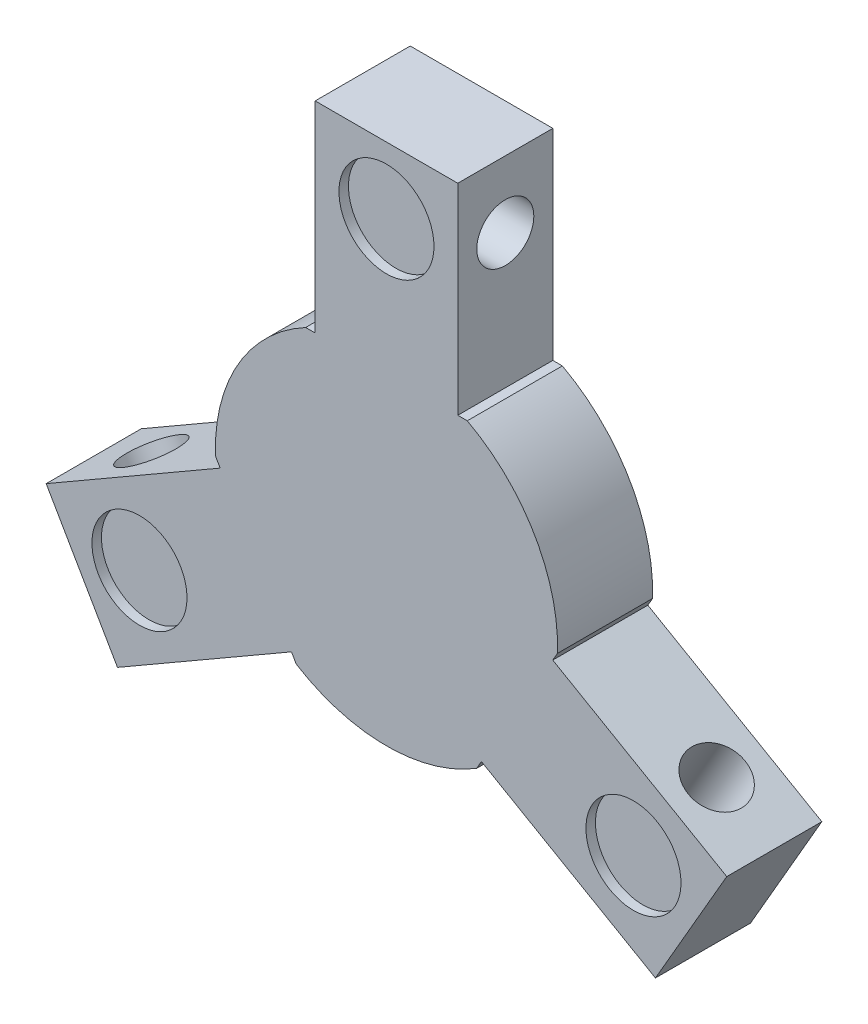
SolidWorks part; units mm, degrees
ref_plane "前视基准面" through (0, 0, 0) normal (0, 0, 1) x (1, 0, 0)
ref_plane "上视基准面" through (0, 0, 0) normal (0, 1, 0) x (1, 0, 0)
ref_plane "右视基准面" through (0, 0, 0) normal (1, 0, 0) x (0, 0, -1)
sketch "草图1" plane through (0, 0, 0) normal (0, 0, 1) x (1, 0, 0)
  line L4 (5, 7.4833) -> (5, 18.0033)
  line L5 (-8.9807, 0.5885) -> (-18.0885, -4.6699)
  line L6 (-3.9807, -8.0718) -> (-13.0885, -13.3301)
  line L7 (3.9807, -8.0718) -> (13.0885, -13.3301)
  line L9 (-5, 18.0033) -> (5, 18.0033)
  line L10 (-18.0885, -4.6699) -> (-13.0885, -13.3301)
  line L11 (18.0885, -4.6699) -> (13.0885, -13.3301)
  line L18 (8.9807, 0.5885) -> (18.0885, -4.6699)
  line L21 (-5, 7.4833) -> (-5, 18.0033)
  arc A0 (-5, 7.4833) -> (-8.9807, 0.5885) centre (0, 0) ccw
  arc A1 (-3.9807, -8.0718) -> (3.9807, -8.0718) centre (0, 0) ccw
  arc A2 (8.9807, 0.5885) -> (5, 7.4833) centre (0, 0) ccw
  dimension "D1" = 18
  dimension "D2" = 10.52
extrude "凸台-拉伸1" add sketch "草图1" along normal blind 5 contours L18 A2 L4 L9 L21 A0 L5 L10 L6 A1 L7 L11
sketch "草图2" plane through (5, 0, 0) normal (1, 0, 0) x (0, 0, -1)
  circle A0 centre (-2.5, 15.0033) radius 1.5
  dimension "D1" = 3
  dimension "D2" = 2.5
  dimension "D3" = 3
extrude "切除-拉伸1" cut sketch "草图2" against normal blind 10
sketch "草图3" plane through (-2.5, -4.3301, 0) normal (-0.5, -0.866, 0) x (0.866, -0.5, 0)
  circle A0 centre (15, 2.5) radius 1.5
  dimension "D1" = 3
  dimension "D2" = 2.5
  dimension "D3" = 3
extrude "切除-拉伸2" cut sketch "草图3" against normal blind 10
sketch "草图4" plane through (2.5, -4.3301, 0) normal (0.5, -0.866, 0) x (0.866, 0.5, 0)
  line L0 (-18, 5) -> (-18, 0) construction
  circle A0 centre (-15, 2.5) radius 1.5
  dimension "D1" = 3
  dimension "D2" = 3
  dimension "D3" = 2.5
extrude "切除-拉伸3" cut sketch "草图4" against normal blind 10
sketch "草图5" plane through (0, 0, 5) normal (0, 0, 1) x (1, 0, 0)
  line L1 (-4, 0) -> (-2, -3.4641)
  line L2 (-2, -3.4641) -> (2, -3.4641)
  line L3 (2, -3.4641) -> (4, 0)
  line L4 (4, 0) -> (2, 3.4641)
  line L5 (2, 3.4641) -> (-2, 3.4641)
  line L6 (-2, 3.4641) -> (-4, 0)
  circle A1 centre (0, 0) radius 3.4641 construction
  dimension "D1" = 4
extrude "切除-拉伸4" cut sketch "草图5" against normal blind 3
sketch "草图6" plane through (0, 0, 5) normal (0, 0, 1) x (1, 0, 0)
  circle A0 centre (0, 0) radius 2.5
  dimension "D1" = 5
extrude "切除-拉伸5" cut sketch "草图6" against normal blind 5
sketch "草图8" plane through (0, 0, 5) normal (0, 0, 1) x (1, 0, 0)
  line L2 (-8.7057, 0.1122) -> (-17.8135, -5.1462)
  line L3 (-8.9998, -0.0576) -> (-17.8135, -5.1462)
  line L5 (-4.2557, -7.5955) -> (-13.3635, -12.8538)
  line L6 (-4.5498, -7.7653) -> (-13.3635, -12.8538)
  line L8 (-4.45, 7.4833) -> (-4.45, 18.0033)
  line L9 (-4.45, 7.8229) -> (-4.45, 18.0033)
  line L11 (4.45, 7.4833) -> (4.45, 18.0033)
  line L12 (4.45, 7.8229) -> (4.45, 18.0033)
  line L14 (4.2557, -7.5955) -> (13.3635, -12.8538)
  line L15 (4.5498, -7.7653) -> (13.3635, -12.8538)
  line L16 (8.9807, 0.5885) -> (18.0885, -4.6699) construction
  line L17 (8.7057, 0.1122) -> (17.8135, -5.1462)
  line L18 (8.9998, -0.0576) -> (17.8135, -5.1462)
  line L19 (18.0885, -4.6699) -> (13.0885, -13.3301) construction
  line L20 (3.9807, -8.0718) -> (13.0885, -13.3301) construction
  line L21 (-3.9807, -8.0718) -> (-13.0885, -13.3301) construction
  line L22 (-8.9807, 0.5885) -> (-18.0885, -4.6699) construction
  line L23 (5, 7.4833) -> (5, 18.0033) construction
  line L24 (-5, 7.4833) -> (-5, 18.0033) construction
  line L25 (-18.0885, -4.6699) -> (-13.0885, -13.3301) construction
  line L26 (-5, 18.0033) -> (5, 18.0033) construction
  line L27 (8.9807, 0.5885) -> (18.0885, -4.6699)
  line L28 (18.0885, -4.6699) -> (17.8135, -5.1462)
  line L29 (3.9807, -8.0718) -> (13.0885, -13.3301)
  line L30 (-3.9807, -8.0718) -> (-13.0885, -13.3301)
  line L31 (-8.9807, 0.5885) -> (-18.0885, -4.6699)
  line L32 (5, 7.4833) -> (5, 18.0033)
  line L33 (-5, 7.4833) -> (-5, 18.0033)
  line L34 (-18.0885, -4.6699) -> (-17.8135, -5.1462)
  line L35 (-5, 18.0033) -> (-4.45, 18.0033)
  line L36 (4.45, 18.0033) -> (5, 18.0033)
  line L37 (13.3635, -12.8538) -> (13.0885, -13.3301)
  line L38 (-13.3635, -12.8538) -> (-13.0885, -13.3301)
  arc A0 (-8.9807, 0.5885) -> (-8.9998, -0.0576) centre (0, 0) ccw
  arc A1 (-4.45, 7.8229) -> (-5, 7.4833) centre (0, 0) ccw
  arc A2 (5, 7.4833) -> (4.45, 7.8229) centre (0, 0) ccw
  arc A3 (8.9998, -0.0576) -> (8.9807, 0.5885) centre (0, 0) ccw
  arc A4 (3.9807, -8.0718) -> (4.5498, -7.7653) centre (0, 0) ccw
  arc A5 (-4.5498, -7.7653) -> (-3.9807, -8.0718) centre (0, 0) ccw
  dimension "D2" = 0.55
  dimension "D3" = 0.55
  dimension "D4" = 0.55
  dimension "0.55" = 0.55
  dimension "D5" = 0.55
  dimension "D6" = 0.55
extrude "切除-拉伸6" cut sketch "草图8" against normal blind 10
sketch "草图9" plane through (0, 0, 0) normal (0, 0, -1) x (-1, 0, 0)
  circle A0 centre (0, 0) radius 2.9
  dimension "D1" = 5.8
extrude "切除-拉伸7" cut sketch "草图9" against normal blind 10
sketch "草图11" plane through (0, 0, 5) normal (0, 0, 1) x (1, 0, 0)
  line L0 (17.8135, -5.1462) -> (13.3635, -12.8538) construction
  line L1 (-4.45, 18.0033) -> (4.45, 18.0033) construction
  line L2 (-4.45, 7.8229) -> (-4.45, 18.0033) construction
  line L3 (4.45, 18.0033) -> (4.45, 7.8229) construction
  line L4 (8.9998, -0.0576) -> (17.8135, -5.1462) construction
  line L5 (13.3635, -12.8538) -> (4.5498, -7.7653) construction
  line L6 (-4.5498, -7.7653) -> (-13.3635, -12.8538) construction
  line L7 (-17.8135, -5.1462) -> (-13.3635, -12.8538) construction
  line L8 (-17.8135, -5.1462) -> (-8.9998, -0.0576) construction
  line L9 (17.8135, -5.1462) -> (17.7135, -5.3194)
  line L10 (-4.45, 18.0033) -> (-4.25, 18.0033)
  line L11 (-4.45, 7.8229) -> (-4.45, 18.0033)
  line L12 (4.45, 18.0033) -> (4.45, 7.8229)
  line L13 (8.9998, -0.0576) -> (17.8135, -5.1462)
  line L14 (13.3635, -12.8538) -> (4.5498, -7.7653)
  line L15 (-4.5498, -7.7653) -> (-13.3635, -12.8538)
  line L16 (-17.8135, -5.1462) -> (-17.7135, -5.3194)
  line L17 (-17.8135, -5.1462) -> (-8.9998, -0.0576)
  line L18 (-17.7135, -5.3194) -> (-8.9955, -0.286)
  line L19 (-4.7455, -7.6473) -> (-13.4635, -12.6806)
  line L20 (-4.25, 7.9333) -> (-4.25, 18.0033)
  line L21 (4.25, 18.0033) -> (4.25, 7.9333)
  line L22 (13.4635, -12.6806) -> (4.7455, -7.6473)
  line L23 (8.9955, -0.286) -> (17.7135, -5.3194)
  line L24 (13.4635, -12.6806) -> (13.3635, -12.8538)
  line L25 (4.25, 18.0033) -> (4.45, 18.0033)
  line L26 (-13.4635, -12.6806) -> (-13.3635, -12.8538)
  line L27 (-4.25, 7.8229) -> (-4.25, 18.0033) construction
  line L28 (4.25, 18.0033) -> (4.25, 7.8229) construction
  line L29 (8.8998, -0.2308) -> (17.7135, -5.3194) construction
  line L30 (13.4635, -12.6806) -> (4.6498, -7.592) construction
  line L31 (-4.6498, -7.592) -> (-13.4635, -12.6806) construction
  line L32 (-17.7135, -5.3194) -> (-8.8998, -0.2308) construction
  arc A0 (-4.25, 7.9333) -> (-4.45, 7.8229) centre (0, 0) ccw
  arc A1 (-8.9998, -0.0576) -> (-8.9955, -0.286) centre (0, 0) ccw
  arc A2 (4.45, 7.8229) -> (4.25, 7.9333) centre (0, 0) ccw
  arc A3 (8.9955, -0.286) -> (8.9998, -0.0576) centre (0, 0) ccw
  arc A4 (-4.7455, -7.6473) -> (-4.5498, -7.7653) centre (0, 0) ccw
  arc A5 (4.5498, -7.7653) -> (4.7455, -7.6473) centre (0, 0) ccw
  dimension "D1" = 0.2
  dimension "D2" = 0.2
  dimension "D3" = 0.2
  dimension "D4" = 0.2
  dimension "D5" = 0.2
  dimension "D6" = 0.2
extrude "切除-拉伸8" cut sketch "草图11" against normal blind 10
sketch "草图12" plane through (0, 0, 5) normal (0, 0, 1) x (1, 0, 0)
  circle A1 centre (0, 15) radius 2.5
  circle A4 centre (12.9904, -7.5) radius 2.5
  circle A5 centre (-12.9904, -7.5) radius 2.5
  dimension "D2" = 5
  dimension "D3" = 5
  dimension "D4" = 5
extrude "切除-拉伸10" cut sketch "草图12" against normal blind 0.5
sketch "草图13" plane through (0, 0, 5) normal (0, 0, 1) x (1, 0, 0)
  circle A4 centre (0, 0) radius 5.7423
extrude "凸台-拉伸2" add sketch "草图13" against normal blind 5
sketch "草图14" plane through (0, 0, 5) normal (0, 0, 1) x (1, 0, 0)
  line L3 (-3.75, 7.9333) -> (-3.75, 18.0033)
  line L4 (-3.75, 7.9333) -> (-3.75, 18.0033)
  line L6 (3.75, 18.0033) -> (3.75, 7.9333)
  line L7 (3.75, 18.0033) -> (3.75, 7.9333)
  line L9 (-17.4635, -5.7524) -> (-8.7455, -0.7191)
  line L10 (-17.4635, -5.7524) -> (-8.7455, -0.7191)
  line L12 (-4.9955, -7.2143) -> (-13.7135, -12.2476)
  line L13 (-4.9955, -7.2143) -> (-13.7135, -12.2476)
  line L15 (13.7135, -12.2476) -> (4.9955, -7.2143)
  line L16 (13.7135, -12.2476) -> (4.9955, -7.2143)
  line L17 (-8.7455, -0.7191) -> (-8.9955, -0.286)
  line L18 (8.7455, -0.7191) -> (17.4635, -5.7524)
  line L19 (8.7455, -0.7191) -> (17.4635, -5.7524)
  line L20 (-8.9955, -0.286) -> (-17.7135, -5.3194)
  line L21 (-17.7135, -5.3194) -> (-17.4635, -5.7524)
  line L22 (-13.7135, -12.2476) -> (-13.4635, -12.6806)
  line L23 (-13.4635, -12.6806) -> (-4.7455, -7.6473)
  line L24 (-4.7455, -7.6473) -> (-4.9955, -7.2143)
  line L25 (4.9955, -7.2143) -> (4.7455, -7.6473)
  line L26 (4.7455, -7.6473) -> (13.4635, -12.6806)
  line L27 (13.4635, -12.6806) -> (13.7135, -12.2476)
  line L28 (8.7455, -0.7191) -> (8.9955, -0.286)
  line L29 (8.9955, -0.286) -> (17.7135, -5.3194)
  line L30 (8.9955, -0.286) -> (17.7135, -5.3194) construction
  line L31 (17.7135, -5.3194) -> (17.4635, -5.7524)
  line L32 (-3.75, 7.9333) -> (-4.25, 7.9333)
  line L33 (-4.25, 7.9333) -> (-4.25, 18.0033)
  line L34 (-4.25, 18.0033) -> (4.25, 18.0033) construction
  line L35 (-4.25, 18.0033) -> (-3.75, 18.0033)
  line L36 (3.75, 18.0033) -> (4.25, 18.0033)
  line L37 (4.25, 18.0033) -> (4.25, 7.9333)
  line L38 (4.25, 7.9333) -> (3.75, 7.9333)
  dimension "D1" = 0.5
  dimension "D2" = 0.5
  dimension "D3" = 0.5
  dimension "D4" = 0.5
  dimension "D5" = 0.5
  dimension "D6" = 0.5
extrude "切除-拉伸11" cut sketch "草图14" against normal blind 5
sketch "草图16" plane through (0, 0, 5) normal (0, 0, 1) x (1, 0, 0)
  line L3 (-3.75, 18.5033) -> (3.75, 18.5033)
  line L4 (-3.75, 18.5033) -> (3.75, 18.5033)
  line L6 (-17.8965, -6.0024) -> (-14.1465, -12.4976)
  line L7 (-17.8965, -6.0024) -> (-14.1465, -12.4976)
  line L8 (-3.75, 18.5033) -> (-3.75, 18.0033)
  line L9 (17.8965, -6.0024) -> (14.1465, -12.4976)
  line L10 (17.8965, -6.0024) -> (14.1465, -12.4976)
  line L11 (-3.75, 18.0033) -> (3.75, 18.0033) construction
  line L12 (-3.75, 18.0033) -> (3.75, 18.0033)
  line L13 (3.75, 18.5033) -> (3.75, 18.0033)
  line L14 (-17.8965, -6.0024) -> (-17.4635, -5.7524)
  line L15 (-17.4635, -5.7524) -> (-8.7455, -0.7191) construction
  line L16 (-17.4635, -5.7524) -> (-13.7135, -12.2476) construction
  line L17 (-17.4635, -5.7524) -> (-13.7135, -12.2476)
  line L18 (-13.7135, -12.2476) -> (-14.1465, -12.4976)
  line L19 (14.1465, -12.4976) -> (13.7135, -12.2476)
  line L20 (13.7135, -12.2476) -> (17.4635, -5.7524)
  line L21 (17.4635, -5.7524) -> (17.8965, -6.0024)
  dimension "D1" = 0.5
  dimension "D2" = 0.5
  dimension "D3" = 0.5
extrude "凸台-拉伸3" add sketch "草图16" against normal blind 5
